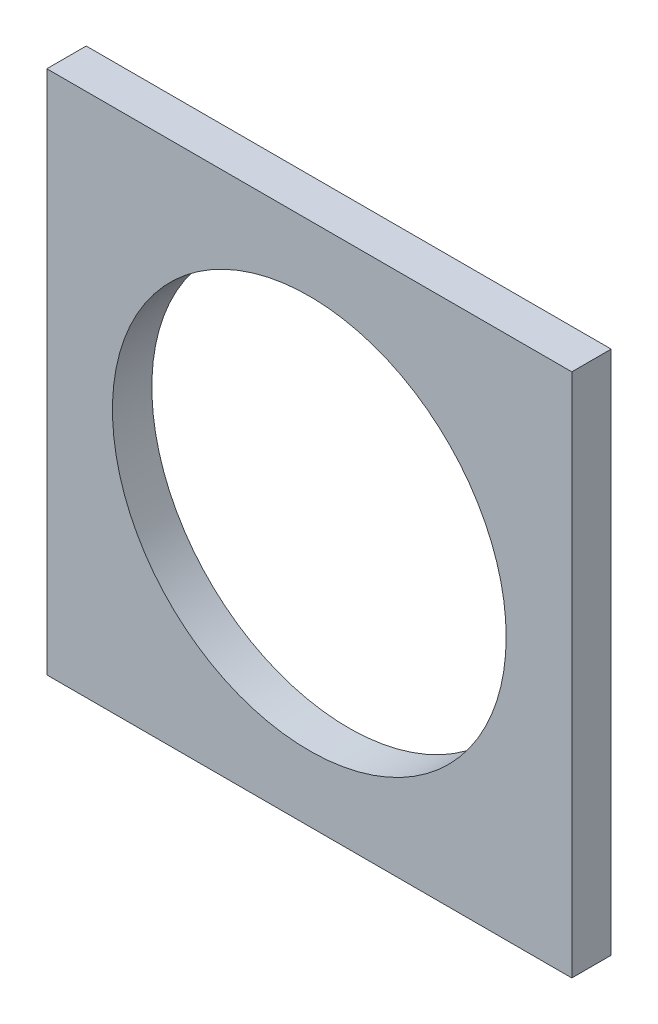
SolidWorks part; units mm, degrees
ref_plane "Front Plane" through (0, 0, 0) normal (0, 0, 1) x (1, 0, 0)
ref_plane "Top Plane" through (0, 0, 0) normal (0, 1, 0) x (1, 0, 0)
ref_plane "Right Plane" through (0, 0, 0) normal (1, 0, 0) x (0, 0, -1)
sketch "Sketch1" plane through (0, 0, 0) normal (0, 0, 1) x (1, 0, 0)
  line L1 (-75, -103.411) -> (-35, -103.411)
  line L2 (-75, -103.411) -> (-75, -143.411)
  line L3 (-75, -143.411) -> (-35, -143.411)
  line L4 (-35, -103.411) -> (-35, -143.411)
  line L8 (-75, -103.411) -> (-35, -143.411) construction
  line L9 (-35, -103.411) -> (-75, -143.411) construction
  circle A0 centre (-55, -123.411) radius 15
  dimension "D1" = 30
  dimension "D2" = 40
extrude "Boss-Extrude1" add sketch "Sketch1" along normal blind 3
